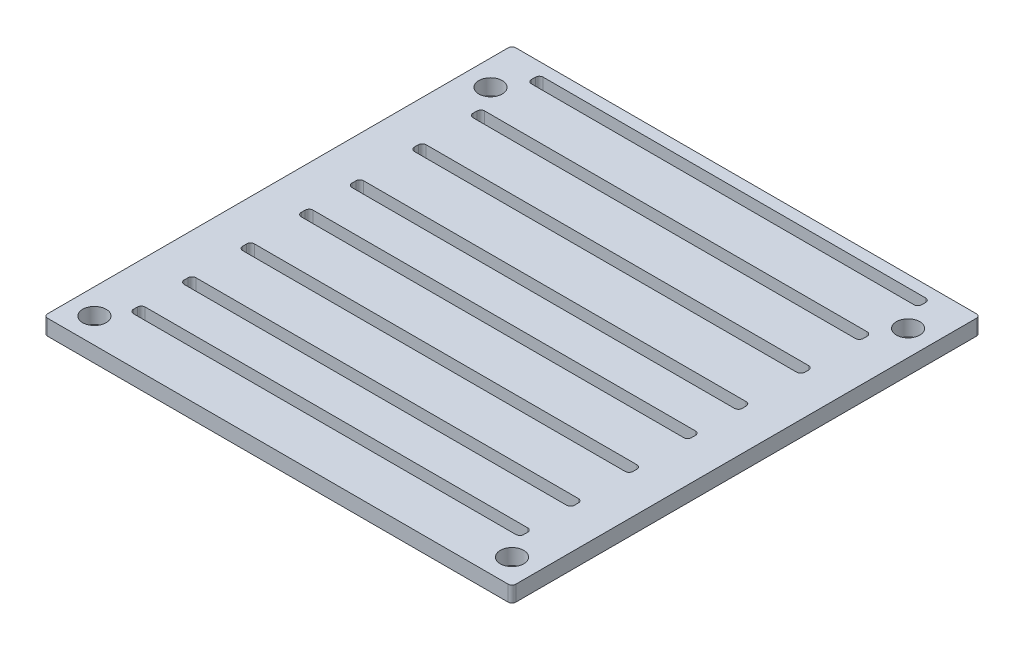
SolidWorks part; units mm, degrees
ref_plane "Front Plane" through (0, 0, 0) normal (0, 0, 1) x (1, 0, 0)
ref_plane "Top Plane" through (0, 0, 0) normal (0, 1, 0) x (1, 0, 0)
ref_plane "Right Plane" through (0, 0, 0) normal (1, 0, 0) x (0, 0, -1)
sketch "Sketch1" plane through (0, 0, 0) normal (0, 1, 0) x (1, 0, 0)
  line L0 (10, 12) -> (10, 15)
  line L1 (0, 0) -> (120, 0)
  line L2 (0, 0) -> (0, 120)
  line L3 (0, 120) -> (120, 120)
  line L4 (120, 0) -> (120, 120)
  line L5 (113.5, 0) -> (113.5, 6.5) construction
  line L6 (6.5, 0) -> (6.5, 6.5) construction
  line L7 (113.5, 120) -> (113.5, 108) construction
  line L8 (10, 68) -> (110, 68)
  line L9 (10, 12) -> (110, 12)
  line L10 (10, 12) -> (10, 15)
  line L11 (10, 15) -> (110, 15)
  line L12 (110, 12) -> (110, 15)
  line L13 (6.5, 120) -> (6.5, 108) construction
  line L15 (10, 25) -> (110, 25)
  line L16 (10, 25) -> (10, 28)
  line L17 (10, 28) -> (110, 28)
  line L18 (110, 25) -> (110, 28)
  line L21 (10, 40) -> (110, 40)
  line L22 (10, 40) -> (10, 43)
  line L23 (10, 43) -> (110, 43)
  line L24 (110, 40) -> (110, 43)
  line L32 (10, 68) -> (10, 71)
  line L33 (10, 55) -> (110, 55)
  line L34 (10, 55) -> (10, 58)
  line L35 (10, 58) -> (110, 58)
  line L36 (110, 55) -> (110, 58)
  line L44 (10, 71) -> (110, 71)
  line L50 (110, 68) -> (110, 71)
  line L51 (10, 84) -> (110, 84)
  line L52 (10, 84) -> (10, 87)
  line L53 (10, 87) -> (110, 87)
  line L54 (110, 84) -> (110, 87)
  line L59 (10, 99) -> (110, 99)
  line L60 (10, 99) -> (10, 102)
  line L61 (10, 102) -> (110, 102)
  line L62 (110, 99) -> (110, 102)
  line L65 (10, 114) -> (110, 114)
  line L66 (10, 114) -> (10, 117)
  line L67 (10, 117) -> (110, 117)
  line L68 (110, 114) -> (110, 117)
  line L72 (10, 84) -> (10, 87)
  line L73 (10, 99) -> (10, 102)
  line L74 (10, 114) -> (10, 117)
  line L80 (110, 15) -> (110, 12)
  line L81 (110, 28) -> (110, 25)
  line L82 (110, 43) -> (110, 40)
  line L85 (10, 25) -> (10, 28)
  line L86 (10, 40) -> (10, 43)
  line L87 (10, 55) -> (10, 58)
  circle A0 centre (113.5, 6.5) radius 3
  circle A1 centre (6.5, 6.5) radius 3
  circle A2 centre (113.5, 108) radius 3
  circle A3 centre (6.5, 108) radius 3
  point P26 (110, 69.5)
  point P39 (110, 115.5)
  dimension "D30" = 6
  dimension "D33" = 6
  dimension "D36" = 6
  dimension "D39" = 6
  dimension "D1" = 120
  dimension "D2" = 120
  dimension "D3" = 10
  dimension "D4" = 100
  dimension "D5" = 12
  dimension "D6" = 3
  dimension "D7" = 25
  dimension "D8" = 3
  dimension "D9" = 40
  dimension "D10" = 3
  dimension "D11" = 3
  dimension "D12" = 68
  dimension "D13" = 55
  dimension "D14" = 3
  dimension "D15" = 84
  dimension "D16" = 3
  dimension "D17" = 3
  dimension "D18" = 99
  dimension "D19" = 3
  dimension "D20" = 114
  dimension "D21" = 100
  dimension "D22" = 100
  dimension "D23" = 100
  dimension "D24" = 100
  dimension "D25" = 100
  dimension "D26" = 100
  dimension "D27" = 100
  dimension "D28" = 6.5
  dimension "D29" = 6.5
  dimension "D31" = 6.5
  dimension "D32" = 6.5
  dimension "D34" = 6.5
  dimension "D35" = 12
  dimension "D37" = 6.5
  dimension "D38" = 12
extrude "Boss-Extrude1" add sketch "Sketch1" against normal blind 4 contours L1 L4 L3 L2 A3 A2 A1 A0 L68 L65 L66 L67 L62 L59 L60 L61 L54 L51 L52 L53 L50 L8 L32 L44 L36 L33 L34 L35 L24 L21 L22 L23 L18 L15 L16 L17 L12 L9 L0
fillet "Fillet1" radius 1 32 edges at (110, -2, -114) (110, -2, -99) (110, -2, -84) (110, -2, -68) (110, -2, -55) (110, -2, -40) (110, -2, -25) (110, -2, -12) (110, -2, -15) (110, -2, -28) (110, -2, -43) (110, -2, -58) (110, -2, -71) (110, -2, -87) (110, -2, -102) (110, -2, -117) (10, -2, -15) (10, -2, -28) (10, -2, -43) (10, -2, -58) (10, -2, -71) (10, -2, -87) (10, -2, -102) (10, -2, -55) (10, -2, -25) (10, -2, -12) (10, -2, -40) (10, -2, -68) (10, -2, -84) (10, -2, -99) (10, -2, -114) (10, -2, -117)
fillet "Fillet2" radius 1 4 edges at (120, -2, 0) (120, -2, -120) (0, -2, -120) (0, -2, 0)
